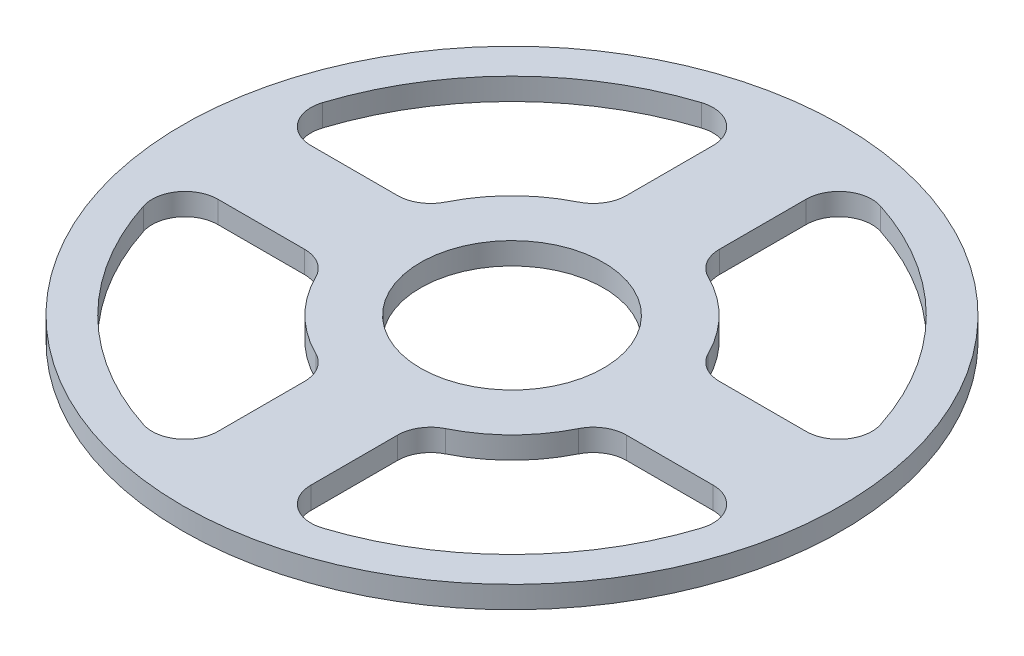
SolidWorks part; units mm, degrees
ref_plane "정면" through (0, 0, 0) normal (0, 0, 1) x (1, 0, 0)
ref_plane "윗면" through (0, 0, 0) normal (0, 1, 0) x (1, 0, 0)
ref_plane "우측면" through (0, 0, 0) normal (1, 0, 0) x (0, 0, -1)
sketch "스케치1" plane through (0, 0, 0) normal (0, 1, 0) x (1, 0, 0)
  circle A0 centre (0, 0) radius 45
  dimension "D1" = 90
extrude "보스-돌출1" add sketch "스케치1" along normal blind 3 contours A0
sketch "스케치2" plane through (0, 3, 0) normal (0, 1, 0) x (1, 0, 0)
  line L0 (0, 45) -> (0, -45) construction
  line L1 (-45, 0) -> (-20, 0) construction
  line L2 (6.35, 39.4928) -> (6.35, 18.9652)
  line L3 (18.9652, 6.35) -> (39.4928, 6.35)
  line L4 (-12.5, 0) -> (45, 0) construction
  line L5 (-6.35, 39.4928) -> (-6.35, 18.9652)
  line L6 (-18.9652, 6.35) -> (-39.4928, 6.35)
  line L7 (6.35, -39.4928) -> (6.35, -18.9652)
  line L8 (18.9652, -6.35) -> (39.4928, -6.35)
  line L9 (-18.9652, -6.35) -> (-39.4928, -6.35)
  line L10 (-6.35, -39.4928) -> (-6.35, -18.9652)
  circle A0 centre (0, 0) radius 12.5
  circle A1 centre (0, 0) radius 45 construction
  arc A2 (18.9652, 6.35) -> (6.35, 18.9652) centre (0, 0) ccw
  arc A3 (39.4928, 6.35) -> (6.35, 39.4928) centre (0, 0) ccw
  arc A4 (-18.9652, 6.35) -> (-6.35, 18.9652) centre (0, 0) cw
  arc A5 (-39.4928, 6.35) -> (-6.35, 39.4928) centre (0, 0) cw
  arc A6 (18.9652, -6.35) -> (6.35, -18.9652) centre (0, 0) cw
  arc A7 (39.4928, -6.35) -> (6.35, -39.4928) centre (0, 0) cw
  arc A8 (-39.4928, -6.35) -> (-6.35, -39.4928) centre (0, 0) ccw
  arc A9 (-18.9652, -6.35) -> (-6.35, -18.9652) centre (0, 0) ccw
  dimension "D1" = 25
  dimension "D2" = 40
  dimension "D3" = 80
  dimension "D4" = 6.35
  dimension "D5" = 6.35
extrude "컷-돌출1" cut sketch "스케치2" against normal through all contours A5 L6 A4 L5 | A0 | A9 L9 A8 L10 | A7 L8 A6 L7 | L3 A3 L2 A2
fillet "필렛1" radius 4.5 16 edges at (39.4928, 1.5, 6.35) (18.9652, 1.5, 6.35) (6.35, 1.5, 18.9652) (6.35, 1.5, 39.4928) (-6.35, 1.5, 39.4928) (-39.4928, 1.5, 6.35) (-6.35, 1.5, 18.9652) (-18.9652, 1.5, 6.35) (-39.4928, 1.5, -6.35) (-6.35, 1.5, -39.4928) (6.35, 1.5, -39.4928) (39.4928, 1.5, -6.35) (-18.9652, 1.5, -6.35) (-6.35, 1.5, -18.9652) (18.9652, 1.5, -6.35) (6.35, 1.5, -18.9652)
